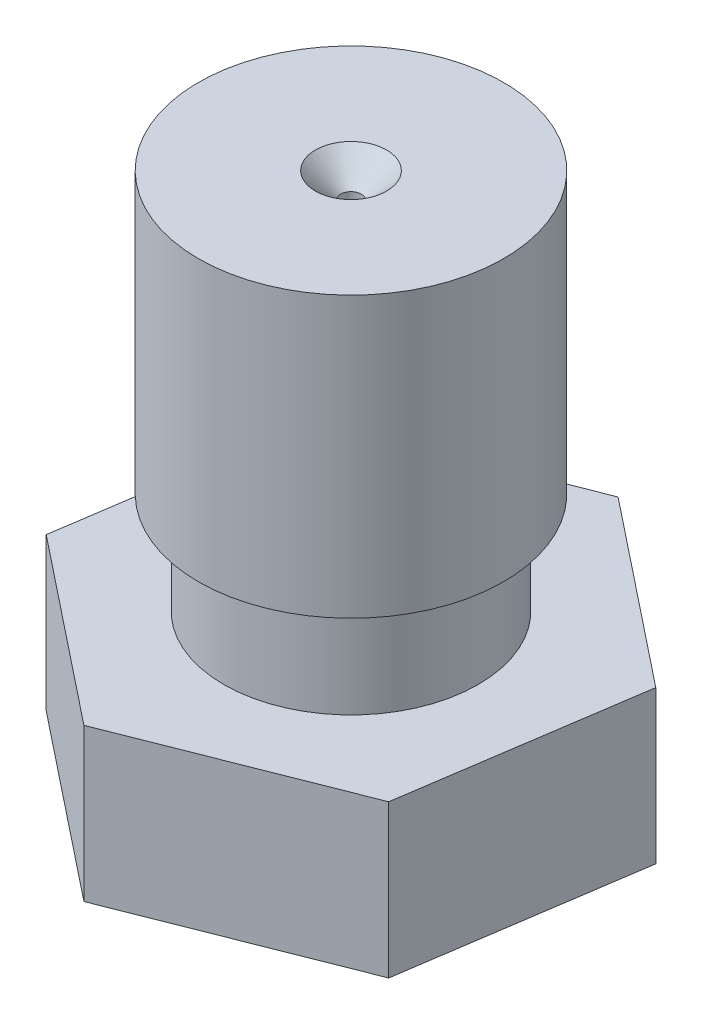
SolidWorks part; units mm, degrees
ref_plane "Front Plane" through (0, 0, 0) normal (0, 0, 1) x (1, 0, 0)
ref_plane "Top Plane" through (0, 0, 0) normal (0, 1, 0) x (1, 0, 0)
ref_plane "Right Plane" through (0, 0, 0) normal (1, 0, 0) x (0, 0, -1)
sketch "Sketch1" plane through (0, 0, 0) normal (0, 0, 1) x (1, 0, 0)
  line L0 (0, 0) -> (0.6, 0) construction
  line L1 (0.2, 0) -> (0.6, 0)
  line L2 (0.6, 0) -> (2.0004, 2)
  line L3 (0.196, 2) -> (5.9295, 2) construction
  line L4 (2.0004, 2) -> (4.696, 2)
  line L5 (4.696, 2) -> (4.696, 5)
  line L6 (4.696, 5) -> (2.5, 5)
  line L7 (2.5, 5) -> (2.5, 7)
  line L8 (2.5, 7) -> (3, 7)
  line L9 (3, 7) -> (3, 12.5)
  line L10 (3, 12.5) -> (0, 12.5) construction
  line L11 (0, 12.5) -> (0, 0) construction
  line L12 (0.2, 0) -> (0.2, 12.5)
  line L13 (0.2, 12.5) -> (3, 12.5)
  dimension "D1" = 0.6
  dimension "D2" = 0.2
  dimension "D3" = 125
  dimension "D4" = 2
  dimension "D5" = 3
  dimension "D6" = 4.5
  dimension "D7" = 3
  dimension "D8" = 0.5
  dimension "D9" = 2
  dimension "D10" = 5.5
revolve "Revolve1" add sketch "Sketch1" angle 360 about L11
chamfer "Chamfer1" distance 0.5 angle 45 1 edges at (0, 12.5, 0.2)
sketch "Sketch2" plane through (0, 5, 0) normal (0, 1, 0) x (1, 0, 0)
  line L1 (-0.6817, -4.5682) -> (3.6153, -2.8745)
  line L2 (3.6153, -2.8745) -> (4.2971, 1.6937)
  line L3 (4.2971, 1.6937) -> (0.6817, 4.5682)
  line L4 (0.6817, 4.5682) -> (-3.6153, 2.8745)
  line L5 (-3.6153, 2.8745) -> (-4.2971, -1.6937)
  line L6 (-4.2971, -1.6937) -> (-0.6817, -4.5682)
  line L7 (11.6358, -2.5339) -> (8.0123, 8.8099)
  line L8 (8.0123, 8.8099) -> (-3.6235, 11.3438)
  line L9 (-3.6235, 11.3438) -> (-11.6358, 2.5339)
  line L10 (-11.6358, 2.5339) -> (-8.0123, -8.8099)
  line L11 (-8.0123, -8.8099) -> (3.6235, -11.3438)
  line L12 (3.6235, -11.3438) -> (11.6358, -2.5339)
  circle A0 centre (0, 0) radius 4 construction
  circle A1 centre (0, 0) radius 10.3131 construction
  dimension "D1" = 8
extrude "Cut-Extrude1" cut sketch "Sketch2" against normal blind 10
equation "\"D2@Sketch1\"=0.4/2"
equation "\"D1@Sketch1\"=1.2/2"
equation "\"D6@Sketch1\"=9/2"
equation "\"D7@Sketch1\"=6/2"
